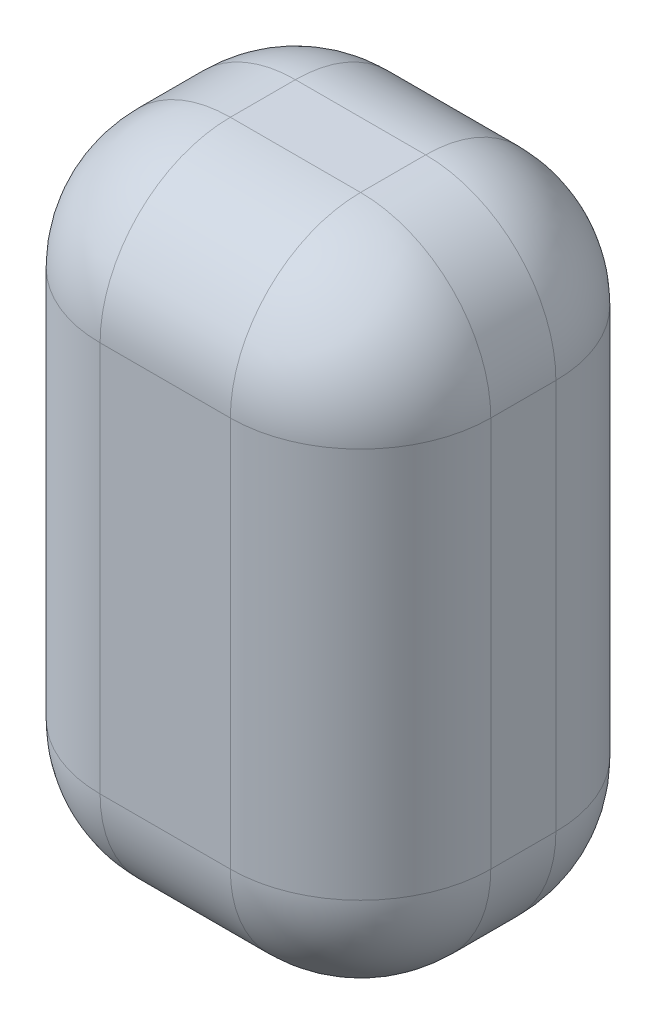
SolidWorks part; units mm, degrees
ref_plane "Front Plane" through (0, 0, 0) normal (0, 0, 1) x (1, 0, 0)
ref_plane "Top Plane" through (0, 0, 0) normal (0, 1, 0) x (1, 0, 0)
ref_plane "Right Plane" through (0, 0, 0) normal (1, 0, 0) x (0, 0, -1)
sketch "Sketch9" plane through (0, 0, 0) normal (0, 1, 0) x (1, 0, 0)
  line L1 (-30, 25) -> (30, 25)
  line L2 (-30, 25) -> (-30, -25)
  line L3 (-30, -25) -> (30, -25)
  line L4 (30, 25) -> (30, -25)
  line L5 (-30, 25) -> (30, -25) construction
  line L6 (-30, -25) -> (30, 25) construction
  point P0 (0, 0)
  dimension "D1" = 60
  dimension "D2" = 50
extrude "Boss-Extrude2" add sketch "Sketch9" along normal blind 100
fillet "Fillet3" radius 20 12 edges at (0, 0, 25) (0, 100, 25) (-30, 100, 0) (-30, 50, 25) (-30, 0, 0) (30, 50, 25) (30, 100, 0) (30, 0, 0) (30, 50, -25) (0, 100, -25) (-30, 50, -25) (0, 0, -25)
